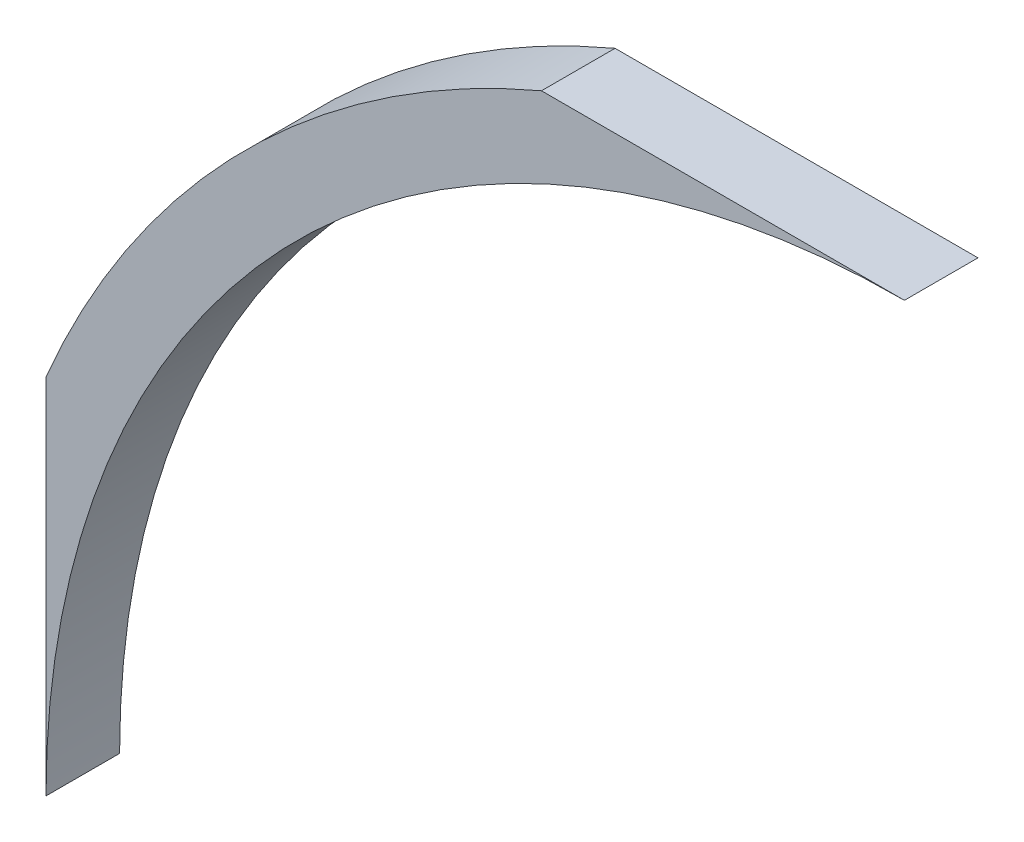
SolidWorks part; units mm, degrees
ref_plane "Front Plane" through (0, 0, 0) normal (1, 0, 0) x (0, 1, 0)
ref_plane "Top Plane" through (0, 0, 0) normal (0, 0, 1) x (0, 1, 0)
ref_plane "Right Plane" through (0, 0, 0) normal (0, 1, 0) x (-1, 0, 0)
sketch "Sketch1" plane through (0, 0, 0) normal (0, 0, 1) x (0, 1, 0)
  line L0 (0, 0) -> (0, 96.4869) construction
  line L1 (0, 0) -> (181.4214, 0) construction
  line L2 (0, 70) -> (29.5973, 70)
  line L3 (70, 0) -> (70, 29.5973)
  arc A0 (70, 0) -> (0, 70) centre (0, 0) ccw
  arc A1 (70, 29.5973) -> (29.5973, 70) centre (0, 0) ccw
  circle A2 centre (0, 0) radius 76 construction
  circle A4 centre (0, 0) radius 70 construction
  dimension "D1" = 140
  dimension "D2" = 6
extrude "Boss-Extrude1" add sketch "Sketch1" along normal blind 6
